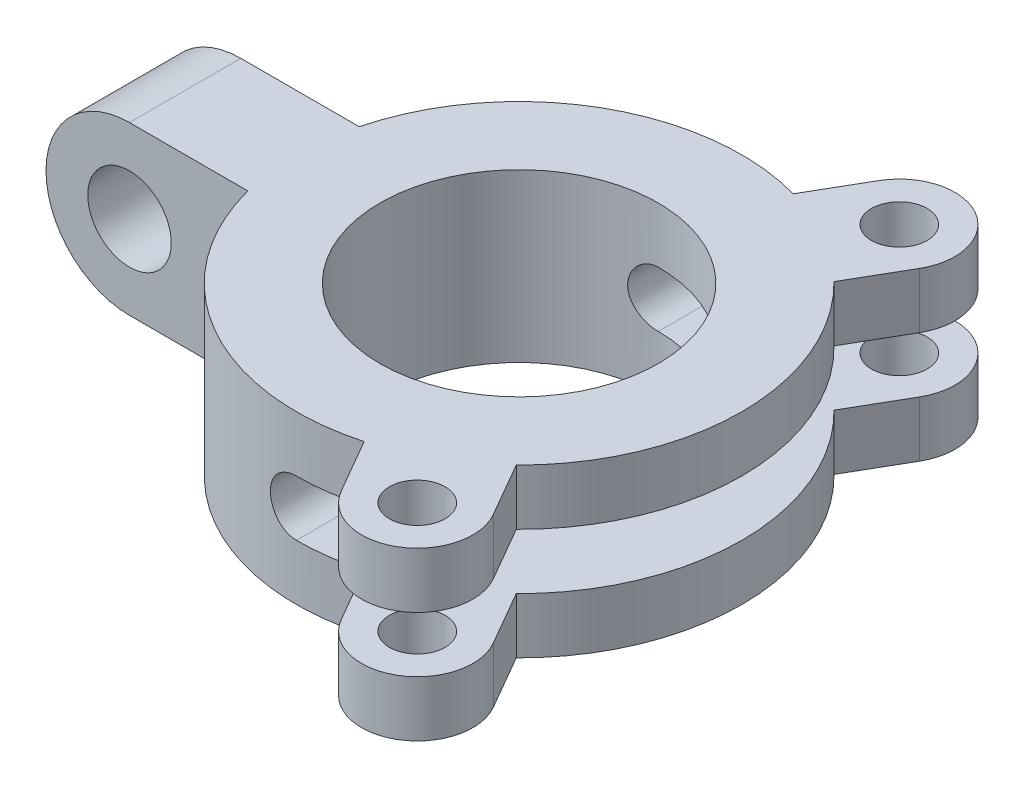
SolidWorks part; units mm, degrees
material "1060 Alloy"
ref_plane "Front Plane" through (0, 0, 0) normal (0, 0, 1) x (1, 0, 0)
ref_plane "Top Plane" through (0, 0, 0) normal (0, 1, 0) x (1, 0, 0)
ref_plane "Right Plane" through (0, 0, 0) normal (1, 0, 0) x (0, 0, -1)
sketch "Sketch1" plane through (0, 0, 0) normal (0, 1, 0) x (1, 0, 0)
  circle A0 centre (0, 0) radius 25
  circle A1 centre (0, 0) radius 40
extrude "Boss-Extrude1" add sketch "Sketch1" along normal mid plane 30 contours A0
sketch "Sketch2" plane through (0, 0, 0) normal (0, 0, 1) x (1, 0, 0)
  line L0 (40, -15) -> (40, 15) construction
  line L1 (40, 5) -> (0, 5)
  line L2 (40, 5) -> (40, -5)
  line L3 (40, -5) -> (0, -5)
  line L4 (0, 5) -> (0, -5)
  circle A0 centre (0, 0) radius 5
  dimension "D1" = 10
  dimension "D2" = 40
  dimension "D3" = 5
extrude "Cut-Extrude1" cut sketch "Sketch2" against normal through all both and the other way through all contours A0 | L3 L4 L1 L2
sketch "Sketch3" plane through (0, 0, 0) normal (0, 1, 0) x (1, 0, 0)
  line L0 (0, 0) -> (69.6999, 0) construction
  line L1 (0, 0) -> (33.3552, -57.7729) construction
  line L2 (16.3397, -48.3013) -> (10.7047, -38.541)
  line L3 (33.6603, -38.3013) -> (28.0252, -28.541)
  circle A0 centre (25, -43.3013) radius 5
  arc A1 (16.3397, -48.3013) -> (33.6603, -38.3013) centre (25, -43.3013) ccw
  circle A2 centre (0, 0) radius 40 construction
  arc A3 (10.7047, -38.541) -> (28.0252, -28.541) centre (0, 0) ccw
  dimension "D2" = 10
  dimension "D3" = 20
  dimension "D4" = 50
extrude "Boss-Extrude2" add sketch "Sketch3" along normal blind 10 from offset 5 contours A1 L3 A3 L2
mirror "Mirror1" about plane through (0, 0, 0) normal (0, 0, 1) of "Boss-Extrude2"
mirror "Mirror2" about plane through (0, 0, 0) normal (0, 1, 0) of "Mirror1", "Boss-Extrude2"
sketch "Sketch4" plane through (0, 0, 0) normal (0, 0, 1) x (1, 0, 0)
  line L0 (0, 0) -> (-75.8638, 0) construction
  line L1 (-25, 15) -> (-25, -15) construction
  line L2 (-60, 15) -> (-25, 15)
  line L4 (-60, -15) -> (-25, -15)
  line L5 (-25, 15) -> (-25, -15)
  circle A0 centre (-60, 0) radius 7.5
  circle A1 centre (-60, 0) radius 15
  point P13 (0, 0)
  dimension "D2" = 15
  dimension "D3" = 60
extrude "Boss-Extrude4" add sketch "Sketch4" along normal mid plane 20 contours A1 L0 A0 | L0 A1 A0 | L0 L5 L2 A1 | L5 L0 A1 L4
equation "\"A\"= 50"
equation "\"B\"= 80"
equation "\"C\"= 30"
equation "\"D1@Sketch1\"=\"A\""
equation "\"D2@Sketch1\"=\"B\""
equation "\"D1@Boss-Extrude1\"=\"C\""
equation "\"D\"= 60'angle"
equation "\"D1@Sketch3\"=\"D\""
equation "\"D1@Sketch4\"=\"C\""
